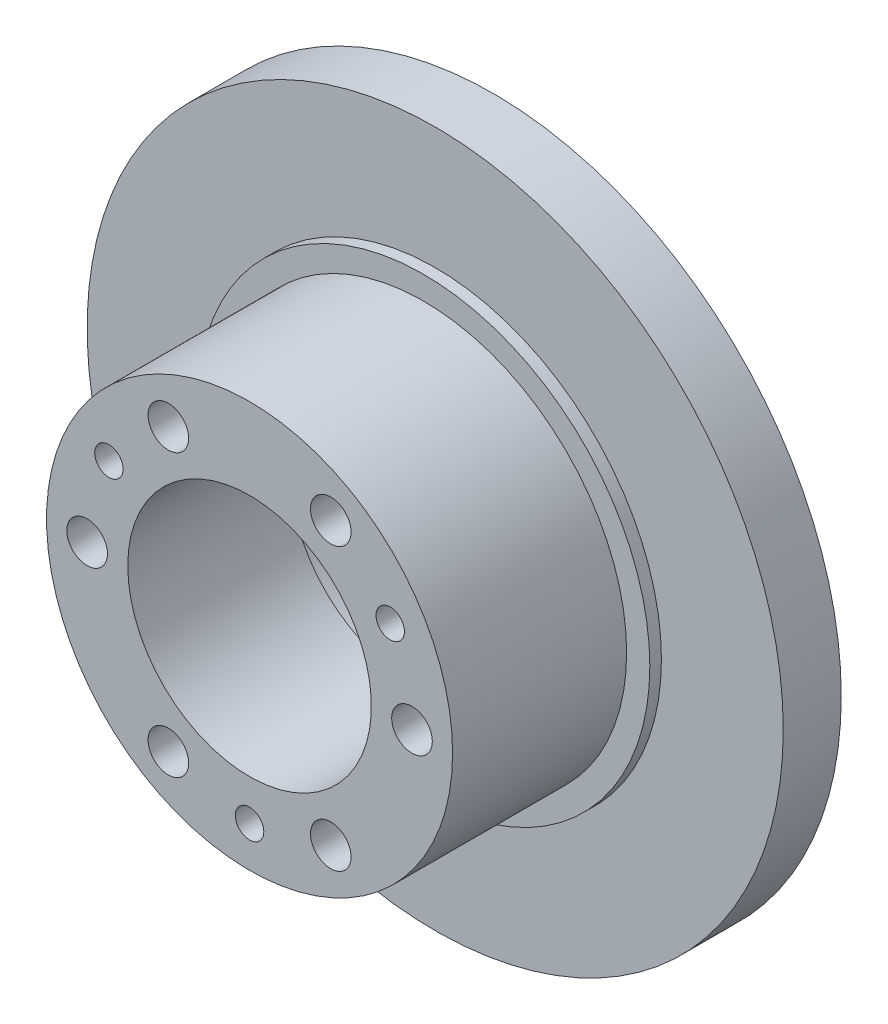
SolidWorks part; units mm, degrees
ref_plane "Front Plane" through (0, 0, 0) normal (0, 0, 1) x (1, 0, 0)
ref_plane "Top Plane" through (0, 0, 0) normal (0, 1, 0) x (1, 0, 0)
ref_plane "Right Plane" through (0, 0, 0) normal (1, 0, 0) x (0, 0, -1)
sketch "Sketch1" plane through (0, 0, 0) normal (0, 0, 1) x (1, 0, 0)
  circle A0 centre (0, 0) radius 30
  dimension "D1" = 60
extrude "Boss-Extrude1" add sketch "Sketch1" along normal blind 5
sketch "Sketch2" plane through (0, 0, 5) normal (0, 0, 1) x (1, 0, 0)
  circle A0 centre (0, 0) radius 19.5
  dimension "D1" = 39
extrude "Boss-Extrude2" add sketch "Sketch2" along normal blind 1
sketch "Sketch3" plane through (0, 0, 6) normal (0, 0, 1) x (1, 0, 0)
  circle A0 centre (0, 0) radius 17.5
  dimension "D1" = 35
extrude "Boss-Extrude3" add sketch "Sketch3" along normal blind 15
sketch "Sketch4" plane through (0, 0, 0) normal (0, 0, -1) x (-1, 0, 0)
  circle A0 centre (0, 0) radius 12.025
  dimension "D1" = 24.05
extrude "Cut-Extrude1" cut sketch "Sketch4" against normal blind 7 contours A0
sketch "Sketch5" plane through (0, 0, 7) normal (0, 0, -1) x (-1, 0, 0)
  circle A0 centre (0, 0) radius 10.5
  dimension "D1" = 21
extrude "Cut-Extrude2" cut sketch "Sketch5" against normal through all
sketch "Sketch6" plane through (0, 0, 5) normal (0, 0, 1) x (1, 0, 0)
  line L0 (0, 0) -> (33.6942, 0) construction
  circle A0 centre (0, 0) radius 24.5 construction
  circle A1 centre (24.5, 0) radius 2
  circle A2 centre (12.25, -21.2176) radius 2
  circle A3 centre (-12.25, -21.2176) radius 2
  circle A4 centre (-24.5, 0) radius 2
  circle A5 centre (-12.25, 21.2176) radius 2
  circle A6 centre (12.25, 21.2176) radius 2
  point P19 (0, 0)
  dimension "D1" = 49
  dimension "D2" = 4
  dimension "D3" = 6
extrude "Cut-Extrude3" cut sketch "Sketch6" against normal blind 4 and the other way blind 4 from surface at -5 starting at face at (-12.025, 0, 0)
sketch "Sketch7" plane through (0, 0, 21) normal (0, 0, 1) x (1, 0, 0)
  line L0 (0, 0) -> (34.5762, 0) construction
  circle A0 centre (0, 0) radius 14 construction
  circle A3 centre (14, 0) radius 1.75
  circle A5 centre (7, -12.1244) radius 1.75
  circle A6 centre (-7, -12.1244) radius 1.75
  circle A7 centre (-14, 0) radius 1.75
  circle A8 centre (-7, 12.1244) radius 1.75
  circle A9 centre (7, 12.1244) radius 1.75
  point P20 (0, 0)
  dimension "D1" = 28
  dimension "D2" = 3.5
  dimension "D3" = 6
extrude "Cut-Extrude4" cut sketch "Sketch7" against normal blind 10
sketch "Sketch8" plane through (0, 0, 21) normal (0, 0, 1) x (1, 0, 0)
  line L0 (0, 0) -> (28.2135, 16.2891) construction
  circle A0 centre (0, 0) radius 14 construction
  circle A1 centre (12.1244, 7) radius 1.225
  circle A2 centre (0, -14) radius 1.225
  circle A3 centre (-12.1244, 7) radius 1.225
  point P4 (12.1244, 7)
  point P15 (0, 0)
  dimension "D1" = 2.45
  dimension "D2" = 3
extrude "Cut-Extrude5" cut sketch "Sketch8" against normal blind 12
